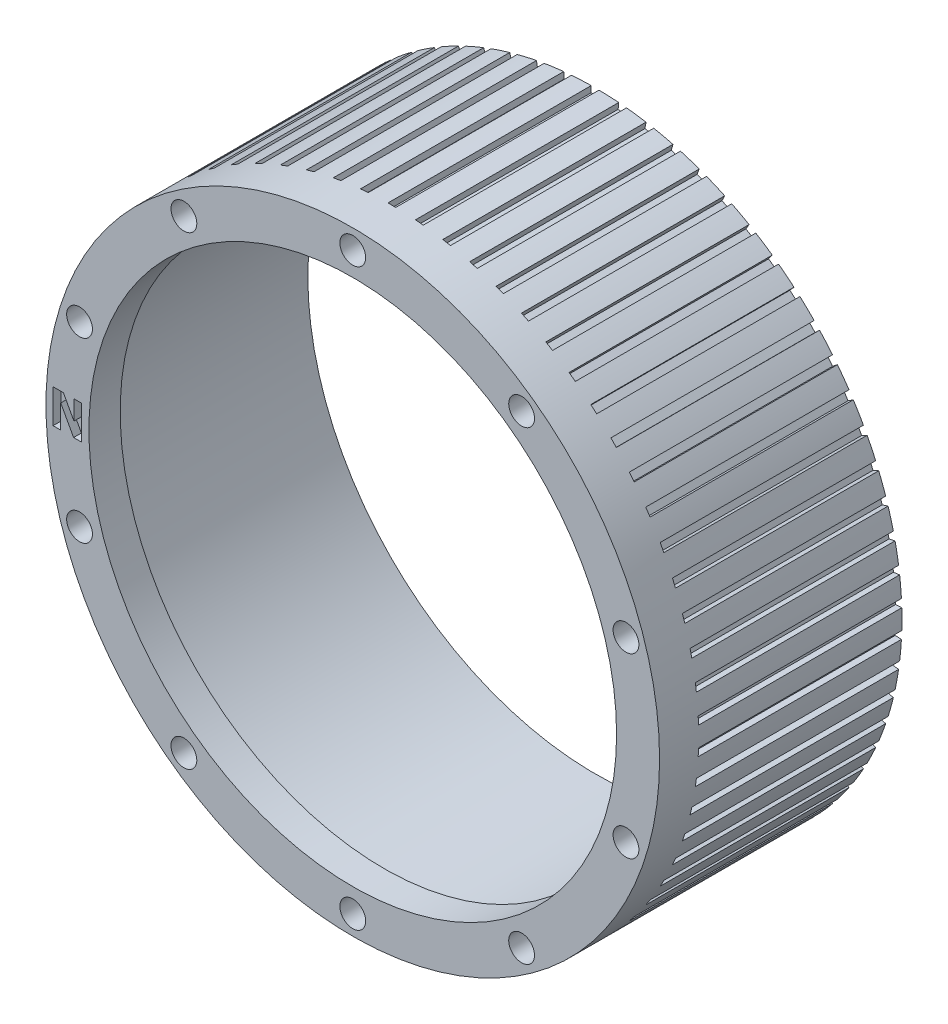
SolidWorks part; units mm, degrees
ref_plane "Front" through (0, 0, 0) normal (0, 0, 1) x (1, 0, 0)
ref_plane "Top" through (0, 0, 0) normal (0, 1, 0) x (1, 0, 0)
ref_plane "Right" through (0, 0, 0) normal (1, 0, 0) x (0, 0, -1)
sketch "Sketch1" plane through (0, 0, 0) normal (0, 0, 1) x (1, 0, 0)
  circle A0 centre (0, 0) radius 36.75 construction
  circle A1 centre (0, 0) radius 39.25
  dimension "D1" = 73.5
  dimension "D2" = 2.5
extrude "Boss-Extrude1" add sketch "Sketch1" along normal blind 31
sketch "Sketch2" plane through (0, 0, 0) normal (0, 0, -1) x (-1, 0, 0)
  circle A0 centre (0, 0) radius 36.75 construction
  circle A1 centre (0, 0) radius 36.75
extrude "Cut-Extrude1" cut sketch "Sketch2" against normal offset from surface (27 mm away) 4 up to face at (39.25, 0, 31)
sketch "Sketch3" plane through (0, 0, 31) normal (0, 0, 1) x (1, 0, 0)
  circle A0 centre (0, 0) radius 36.75 construction
  circle A1 centre (0, 0) radius 36.75 construction
  circle A2 centre (0, 0) radius 33.75
  dimension "D1" = 3
extrude "Cut-Extrude2" cut sketch "Sketch3" against normal up to surface (4 mm away) up to face at (36.75, 0, 27)
sketch "Sketch4" plane through (0, 0, 31) normal (0, 0, 1) x (1, 0, 0)
  line L0 (0, 0) -> (0, 39.25) construction
  circle A0 centre (0, 0) radius 36.75 construction
  circle A1 centre (0, 0) radius 36.75 construction
  circle A2 centre (-34.9513, -11.3564) radius 1.65
  circle A3 centre (0, 0) radius 36.75 construction
  circle A4 centre (-34.9513, 11.3564) radius 1.65
  circle A5 centre (0, 0) radius 36.75 construction
  circle A6 centre (-21.6011, 29.7314) radius 1.65
  circle A7 centre (0, 0) radius 36.75 construction
  circle A8 centre (0, 36.75) radius 1.65
  circle A9 centre (0, 0) radius 36.75 construction
  circle A10 centre (21.6011, 29.7314) radius 1.65
  circle A11 centre (0, 0) radius 36.75 construction
  circle A12 centre (34.9513, 11.3564) radius 1.65
  circle A13 centre (0, 0) radius 36.75 construction
  circle A14 centre (34.9513, -11.3564) radius 1.65
  circle A15 centre (0, 0) radius 36.75 construction
  circle A16 centre (21.6011, -29.7314) radius 1.65
  circle A17 centre (0, 0) radius 36.75 construction
  circle A18 centre (0, -36.75) radius 1.65
  circle A19 centre (0, 0) radius 36.75 construction
  circle A20 centre (-21.6011, -29.7314) radius 1.65
  circle A21 centre (0, 0) radius 39.25 construction
  dimension "D1" = 3.3
  dimension "D3" = 21.6011
  dimension "D2" = 10
extrude "Cut-Extrude3" cut sketch "Sketch4" against normal blind 2.5
sketch "Sketch5" plane through (0, 0, 0) normal (0, 0, -1) x (-1, 0, 0)
  line L0 (0, 0) -> (0, 39.25) construction
  line L1 (-0.5, 39.25) -> (0.5, 39.25)
  line L2 (-0.5, 39.25) -> (-0.5, 38.45)
  line L3 (-0.5, 38.45) -> (0.5, 38.45)
  line L4 (0.5, 39.25) -> (0.5, 38.45)
  line L5 (-0.5, 39.25) -> (0.5, 38.45) construction
  line L6 (-0.5, 38.45) -> (0.5, 39.25) construction
  line L7 (3.0204, 39.1368) -> (2.9486, 38.34)
  line L8 (3.0204, 39.1368) -> (4.0163, 39.0472)
  line L9 (4.0163, 39.0472) -> (3.9446, 38.2504)
  line L10 (2.9486, 38.34) -> (3.9446, 38.2504)
  line L11 (6.5164, 38.7085) -> (6.3735, 37.9214)
  line L12 (6.5164, 38.7085) -> (7.5003, 38.53)
  line L13 (7.5003, 38.53) -> (7.3575, 37.7428)
  line L14 (6.3735, 37.9214) -> (7.3575, 37.7428)
  line L15 (9.96, 37.9686) -> (9.7471, 37.1974)
  line L16 (9.96, 37.9686) -> (10.9239, 37.7025)
  line L17 (10.9239, 37.7025) -> (10.7111, 36.9314)
  line L18 (9.7471, 37.1974) -> (10.7111, 36.9314)
  line L19 (13.3233, 36.9229) -> (13.0422, 36.1739)
  line L20 (13.3233, 36.9229) -> (14.2596, 36.5715)
  line L21 (14.2596, 36.5715) -> (13.9785, 35.8225)
  line L22 (13.0422, 36.1739) -> (13.9785, 35.8225)
  line L23 (16.5795, 35.58) -> (16.2323, 34.8592)
  line L24 (16.5795, 35.58) -> (17.4804, 35.1461)
  line L25 (17.4804, 35.1461) -> (17.1333, 34.4253)
  line L26 (16.2323, 34.8592) -> (17.1333, 34.4253)
  line L27 (19.7021, 33.9506) -> (19.2918, 33.2638)
  line L28 (19.7021, 33.9506) -> (20.5605, 33.4377)
  line L29 (20.5605, 33.4377) -> (20.1502, 32.7509)
  line L30 (19.2918, 33.2638) -> (20.1502, 32.7509)
  line L31 (22.6661, 32.0478) -> (22.1958, 31.4006)
  line L32 (22.6661, 32.0478) -> (23.4751, 31.46)
  line L33 (23.4751, 31.46) -> (23.0049, 30.8128)
  line L34 (22.1958, 31.4006) -> (23.0049, 30.8128)
  line L35 (25.4476, 29.887) -> (24.9212, 29.2846)
  line L36 (25.4476, 29.887) -> (26.2006, 29.2291)
  line L37 (26.2006, 29.2291) -> (25.6743, 28.6266)
  line L38 (24.9212, 29.2846) -> (25.6743, 28.6266)
  line L39 (28.0242, 27.4856) -> (27.4459, 26.9328)
  line L40 (28.0242, 27.4856) -> (28.7152, 26.7628)
  line L41 (28.7152, 26.7628) -> (28.137, 26.21)
  line L42 (27.4459, 26.9328) -> (28.137, 26.21)
  line L43 (30.3751, 24.8629) -> (29.7497, 24.3641)
  line L44 (30.3751, 24.8629) -> (30.9986, 24.0811)
  line L45 (30.9986, 24.0811) -> (30.3732, 23.5823)
  line L46 (29.7497, 24.3641) -> (30.3732, 23.5823)
  line L47 (32.4816, 22.04) -> (31.8139, 21.5993)
  line L48 (32.4816, 22.04) -> (33.0324, 21.2054)
  line L49 (33.0324, 21.2054) -> (32.3648, 20.7647)
  line L50 (31.8139, 21.5993) -> (32.3648, 20.7647)
  line L51 (34.3264, 19.0396) -> (33.622, 18.6605)
  line L52 (34.3264, 19.0396) -> (34.8003, 18.159)
  line L53 (34.8003, 18.159) -> (34.0958, 17.78)
  line L54 (33.622, 18.6605) -> (34.0958, 17.78)
  line L55 (35.895, 15.886) -> (35.1593, 15.5716)
  line L56 (35.895, 15.886) -> (36.288, 14.9665)
  line L57 (36.288, 14.9665) -> (35.5524, 14.652)
  line L58 (35.1593, 15.5716) -> (35.5524, 14.652)
  line L59 (37.1745, 12.6044) -> (36.4136, 12.3572)
  line L60 (37.1745, 12.6044) -> (37.4835, 11.6534)
  line L61 (37.4835, 11.6534) -> (36.7226, 11.4062)
  line L62 (36.4136, 12.3572) -> (36.7226, 11.4062)
  line L63 (38.1547, 9.2214) -> (37.3747, 9.0434)
  line L64 (38.1547, 9.2214) -> (38.3772, 8.2465)
  line L65 (38.3772, 8.2465) -> (37.5972, 8.0685)
  line L66 (37.3747, 9.0434) -> (37.5972, 8.0685)
  line L67 (38.8277, 5.7641) -> (38.0349, 5.6567)
  line L68 (38.8277, 5.7641) -> (38.9619, 4.7732)
  line L69 (38.9619, 4.7732) -> (38.1691, 4.6658)
  line L70 (38.0349, 5.6567) -> (38.1691, 4.6658)
  line L71 (39.188, 2.2604) -> (38.3889, 2.2245)
  line L72 (39.188, 2.2604) -> (39.2329, 1.2614)
  line L73 (39.2329, 1.2614) -> (38.4337, 1.2256)
  line L74 (38.3889, 2.2245) -> (38.4337, 1.2256)
  line L75 (39.2329, -1.2614) -> (38.4337, -1.2256)
  line L76 (39.2329, -1.2614) -> (39.188, -2.2604)
  line L77 (39.188, -2.2604) -> (38.3889, -2.2245)
  line L78 (38.4337, -1.2256) -> (38.3889, -2.2245)
  line L79 (38.9619, -4.7732) -> (38.1691, -4.6658)
  line L80 (38.9619, -4.7732) -> (38.8277, -5.7641)
  line L81 (38.8277, -5.7641) -> (38.0349, -5.6567)
  line L82 (38.1691, -4.6658) -> (38.0349, -5.6567)
  line L83 (38.3772, -8.2465) -> (37.5972, -8.0685)
  line L84 (38.3772, -8.2465) -> (38.1547, -9.2214)
  line L85 (38.1547, -9.2214) -> (37.3747, -9.0434)
  line L86 (37.5972, -8.0685) -> (37.3747, -9.0434)
  line L87 (37.4835, -11.6534) -> (36.7226, -11.4062)
  line L88 (37.4835, -11.6534) -> (37.1745, -12.6044)
  line L89 (37.1745, -12.6044) -> (36.4136, -12.3572)
  line L90 (36.7226, -11.4062) -> (36.4136, -12.3572)
  line L91 (36.288, -14.9665) -> (35.5524, -14.652)
  line L92 (36.288, -14.9665) -> (35.895, -15.886)
  line L93 (35.895, -15.886) -> (35.1593, -15.5716)
  line L94 (35.5524, -14.652) -> (35.1593, -15.5716)
  line L95 (34.8003, -18.159) -> (34.0958, -17.78)
  line L96 (34.8003, -18.159) -> (34.3264, -19.0396)
  line L97 (34.3264, -19.0396) -> (33.622, -18.6605)
  line L98 (34.0958, -17.78) -> (33.622, -18.6605)
  line L99 (33.0324, -21.2054) -> (32.3648, -20.7647)
  line L100 (33.0324, -21.2054) -> (32.4816, -22.04)
  line L101 (32.4816, -22.04) -> (31.8139, -21.5993)
  line L102 (32.3648, -20.7647) -> (31.8139, -21.5993)
  line L103 (30.9986, -24.0811) -> (30.3732, -23.5823)
  line L104 (30.9986, -24.0811) -> (30.3751, -24.8629)
  line L105 (30.3751, -24.8629) -> (29.7497, -24.3641)
  line L106 (30.3732, -23.5823) -> (29.7497, -24.3641)
  line L107 (28.7152, -26.7628) -> (28.137, -26.21)
  line L108 (28.7152, -26.7628) -> (28.0242, -27.4856)
  line L109 (28.0242, -27.4856) -> (27.4459, -26.9328)
  line L110 (28.137, -26.21) -> (27.4459, -26.9328)
  line L111 (26.2006, -29.2291) -> (25.6743, -28.6266)
  line L112 (26.2006, -29.2291) -> (25.4476, -29.887)
  line L113 (25.4476, -29.887) -> (24.9212, -29.2846)
  line L114 (25.6743, -28.6266) -> (24.9212, -29.2846)
  line L115 (23.4751, -31.46) -> (23.0049, -30.8128)
  line L116 (23.4751, -31.46) -> (22.6661, -32.0478)
  line L117 (22.6661, -32.0478) -> (22.1958, -31.4006)
  line L118 (23.0049, -30.8128) -> (22.1958, -31.4006)
  line L119 (20.5605, -33.4377) -> (20.1502, -32.7509)
  line L120 (20.5605, -33.4377) -> (19.7021, -33.9506)
  line L121 (19.7021, -33.9506) -> (19.2918, -33.2638)
  line L122 (20.1502, -32.7509) -> (19.2918, -33.2638)
  line L123 (17.4804, -35.1461) -> (17.1333, -34.4253)
  line L124 (17.4804, -35.1461) -> (16.5795, -35.58)
  line L125 (16.5795, -35.58) -> (16.2323, -34.8592)
  line L126 (17.1333, -34.4253) -> (16.2323, -34.8592)
  line L127 (14.2596, -36.5715) -> (13.9785, -35.8225)
  line L128 (14.2596, -36.5715) -> (13.3233, -36.9229)
  line L129 (13.3233, -36.9229) -> (13.0422, -36.1739)
  line L130 (13.9785, -35.8225) -> (13.0422, -36.1739)
  line L131 (10.9239, -37.7025) -> (10.7111, -36.9314)
  line L132 (10.9239, -37.7025) -> (9.96, -37.9686)
  line L133 (9.96, -37.9686) -> (9.7471, -37.1974)
  line L134 (10.7111, -36.9314) -> (9.7471, -37.1974)
  line L135 (7.5003, -38.53) -> (7.3575, -37.7428)
  line L136 (7.5003, -38.53) -> (6.5164, -38.7085)
  line L137 (6.5164, -38.7085) -> (6.3735, -37.9214)
  line L138 (7.3575, -37.7428) -> (6.3735, -37.9214)
  line L139 (4.0163, -39.0472) -> (3.9446, -38.2504)
  line L140 (4.0163, -39.0472) -> (3.0204, -39.1368)
  line L141 (3.0204, -39.1368) -> (2.9486, -38.34)
  line L142 (3.9446, -38.2504) -> (2.9486, -38.34)
  line L143 (0.5, -39.25) -> (0.5, -38.45)
  line L144 (0.5, -39.25) -> (-0.5, -39.25)
  line L145 (-0.5, -39.25) -> (-0.5, -38.45)
  line L146 (0.5, -38.45) -> (-0.5, -38.45)
  line L147 (-3.0204, -39.1368) -> (-2.9486, -38.34)
  line L148 (-3.0204, -39.1368) -> (-4.0163, -39.0472)
  line L149 (-4.0163, -39.0472) -> (-3.9446, -38.2504)
  line L150 (-2.9486, -38.34) -> (-3.9446, -38.2504)
  line L151 (-6.5164, -38.7085) -> (-6.3735, -37.9214)
  line L152 (-6.5164, -38.7085) -> (-7.5003, -38.53)
  line L153 (-7.5003, -38.53) -> (-7.3575, -37.7428)
  line L154 (-6.3735, -37.9214) -> (-7.3575, -37.7428)
  line L155 (-9.96, -37.9686) -> (-9.7471, -37.1974)
  line L156 (-9.96, -37.9686) -> (-10.9239, -37.7025)
  line L157 (-10.9239, -37.7025) -> (-10.7111, -36.9314)
  line L158 (-9.7471, -37.1974) -> (-10.7111, -36.9314)
  line L159 (-13.3233, -36.9229) -> (-13.0422, -36.1739)
  line L160 (-13.3233, -36.9229) -> (-14.2596, -36.5715)
  line L161 (-14.2596, -36.5715) -> (-13.9785, -35.8225)
  line L162 (-13.0422, -36.1739) -> (-13.9785, -35.8225)
  line L163 (-16.5795, -35.58) -> (-16.2323, -34.8592)
  line L164 (-16.5795, -35.58) -> (-17.4804, -35.1461)
  line L165 (-17.4804, -35.1461) -> (-17.1333, -34.4253)
  line L166 (-16.2323, -34.8592) -> (-17.1333, -34.4253)
  line L167 (-19.7021, -33.9506) -> (-19.2918, -33.2638)
  line L168 (-19.7021, -33.9506) -> (-20.5605, -33.4377)
  line L169 (-20.5605, -33.4377) -> (-20.1502, -32.7509)
  line L170 (-19.2918, -33.2638) -> (-20.1502, -32.7509)
  line L171 (-22.6661, -32.0478) -> (-22.1958, -31.4006)
  line L172 (-22.6661, -32.0478) -> (-23.4751, -31.46)
  line L173 (-23.4751, -31.46) -> (-23.0049, -30.8128)
  line L174 (-22.1958, -31.4006) -> (-23.0049, -30.8128)
  line L175 (-25.4476, -29.887) -> (-24.9212, -29.2846)
  line L176 (-25.4476, -29.887) -> (-26.2006, -29.2291)
  line L177 (-26.2006, -29.2291) -> (-25.6743, -28.6266)
  line L178 (-24.9212, -29.2846) -> (-25.6743, -28.6266)
  line L179 (-28.0242, -27.4856) -> (-27.4459, -26.9328)
  line L180 (-28.0242, -27.4856) -> (-28.7152, -26.7628)
  line L181 (-28.7152, -26.7628) -> (-28.137, -26.21)
  line L182 (-27.4459, -26.9328) -> (-28.137, -26.21)
  line L183 (-30.3751, -24.8629) -> (-29.7497, -24.3641)
  line L184 (-30.3751, -24.8629) -> (-30.9986, -24.0811)
  line L185 (-30.9986, -24.0811) -> (-30.3732, -23.5823)
  line L186 (-29.7497, -24.3641) -> (-30.3732, -23.5823)
  line L187 (-32.4816, -22.04) -> (-31.8139, -21.5993)
  line L188 (-32.4816, -22.04) -> (-33.0324, -21.2054)
  line L189 (-33.0324, -21.2054) -> (-32.3648, -20.7647)
  line L190 (-31.8139, -21.5993) -> (-32.3648, -20.7647)
  line L191 (-34.3264, -19.0396) -> (-33.622, -18.6605)
  line L192 (-34.3264, -19.0396) -> (-34.8003, -18.159)
  line L193 (-34.8003, -18.159) -> (-34.0958, -17.78)
  line L194 (-33.622, -18.6605) -> (-34.0958, -17.78)
  line L195 (-35.895, -15.886) -> (-35.1593, -15.5716)
  line L196 (-35.895, -15.886) -> (-36.288, -14.9665)
  line L197 (-36.288, -14.9665) -> (-35.5524, -14.652)
  line L198 (-35.1593, -15.5716) -> (-35.5524, -14.652)
  line L199 (-37.1745, -12.6044) -> (-36.4136, -12.3572)
  line L200 (-37.1745, -12.6044) -> (-37.4835, -11.6534)
  line L201 (-37.4835, -11.6534) -> (-36.7226, -11.4062)
  line L202 (-36.4136, -12.3572) -> (-36.7226, -11.4062)
  line L203 (-38.1547, -9.2214) -> (-37.3747, -9.0434)
  line L204 (-38.1547, -9.2214) -> (-38.3772, -8.2465)
  line L205 (-38.3772, -8.2465) -> (-37.5972, -8.0685)
  line L206 (-37.3747, -9.0434) -> (-37.5972, -8.0685)
  line L207 (-38.8277, -5.7641) -> (-38.0349, -5.6567)
  line L208 (-38.8277, -5.7641) -> (-38.9619, -4.7732)
  line L209 (-38.9619, -4.7732) -> (-38.1691, -4.6658)
  line L210 (-38.0349, -5.6567) -> (-38.1691, -4.6658)
  line L211 (-39.188, -2.2604) -> (-38.3889, -2.2245)
  line L212 (-39.188, -2.2604) -> (-39.2329, -1.2614)
  line L213 (-39.2329, -1.2614) -> (-38.4337, -1.2256)
  line L214 (-38.3889, -2.2245) -> (-38.4337, -1.2256)
  line L215 (-39.2329, 1.2614) -> (-38.4337, 1.2256)
  line L216 (-39.2329, 1.2614) -> (-39.188, 2.2604)
  line L217 (-39.188, 2.2604) -> (-38.3889, 2.2245)
  line L218 (-38.4337, 1.2256) -> (-38.3889, 2.2245)
  line L219 (-38.9619, 4.7732) -> (-38.1691, 4.6658)
  line L220 (-38.9619, 4.7732) -> (-38.8277, 5.7641)
  line L221 (-38.8277, 5.7641) -> (-38.0349, 5.6567)
  line L222 (-38.1691, 4.6658) -> (-38.0349, 5.6567)
  line L223 (-38.3772, 8.2465) -> (-37.5972, 8.0685)
  line L224 (-38.3772, 8.2465) -> (-38.1547, 9.2214)
  line L225 (-38.1547, 9.2214) -> (-37.3747, 9.0434)
  line L226 (-37.5972, 8.0685) -> (-37.3747, 9.0434)
  line L227 (-37.4835, 11.6534) -> (-36.7226, 11.4062)
  line L228 (-37.4835, 11.6534) -> (-37.1745, 12.6044)
  line L229 (-37.1745, 12.6044) -> (-36.4136, 12.3572)
  line L230 (-36.7226, 11.4062) -> (-36.4136, 12.3572)
  line L231 (-36.288, 14.9665) -> (-35.5524, 14.652)
  line L232 (-36.288, 14.9665) -> (-35.895, 15.886)
  line L233 (-35.895, 15.886) -> (-35.1593, 15.5716)
  line L234 (-35.5524, 14.652) -> (-35.1593, 15.5716)
  line L235 (-34.8003, 18.159) -> (-34.0958, 17.78)
  line L236 (-34.8003, 18.159) -> (-34.3264, 19.0396)
  line L237 (-34.3264, 19.0396) -> (-33.622, 18.6605)
  line L238 (-34.0958, 17.78) -> (-33.622, 18.6605)
  line L239 (-33.0324, 21.2054) -> (-32.3648, 20.7647)
  line L240 (-33.0324, 21.2054) -> (-32.4816, 22.04)
  line L241 (-32.4816, 22.04) -> (-31.8139, 21.5993)
  line L242 (-32.3648, 20.7647) -> (-31.8139, 21.5993)
  line L243 (-30.9986, 24.0811) -> (-30.3732, 23.5823)
  line L244 (-30.9986, 24.0811) -> (-30.3751, 24.8629)
  line L245 (-30.3751, 24.8629) -> (-29.7497, 24.3641)
  line L246 (-30.3732, 23.5823) -> (-29.7497, 24.3641)
  line L247 (-28.7152, 26.7628) -> (-28.137, 26.21)
  line L248 (-28.7152, 26.7628) -> (-28.0242, 27.4856)
  line L249 (-28.0242, 27.4856) -> (-27.4459, 26.9328)
  line L250 (-28.137, 26.21) -> (-27.4459, 26.9328)
  line L251 (-26.2006, 29.2291) -> (-25.6743, 28.6266)
  line L252 (-26.2006, 29.2291) -> (-25.4476, 29.887)
  line L253 (-25.4476, 29.887) -> (-24.9212, 29.2846)
  line L254 (-25.6743, 28.6266) -> (-24.9212, 29.2846)
  line L255 (-23.4751, 31.46) -> (-23.0049, 30.8128)
  line L256 (-23.4751, 31.46) -> (-22.6661, 32.0478)
  line L257 (-22.6661, 32.0478) -> (-22.1958, 31.4006)
  line L258 (-23.0049, 30.8128) -> (-22.1958, 31.4006)
  line L259 (-20.5605, 33.4377) -> (-20.1502, 32.7509)
  line L260 (-20.5605, 33.4377) -> (-19.7021, 33.9506)
  line L261 (-19.7021, 33.9506) -> (-19.2918, 33.2638)
  line L262 (-20.1502, 32.7509) -> (-19.2918, 33.2638)
  line L263 (-17.4804, 35.1461) -> (-17.1333, 34.4253)
  line L264 (-17.4804, 35.1461) -> (-16.5795, 35.58)
  line L265 (-16.5795, 35.58) -> (-16.2323, 34.8592)
  line L266 (-17.1333, 34.4253) -> (-16.2323, 34.8592)
  line L267 (-14.2596, 36.5715) -> (-13.9785, 35.8225)
  line L268 (-14.2596, 36.5715) -> (-13.3233, 36.9229)
  line L269 (-13.3233, 36.9229) -> (-13.0422, 36.1739)
  line L270 (-13.9785, 35.8225) -> (-13.0422, 36.1739)
  line L271 (-10.9239, 37.7025) -> (-10.7111, 36.9314)
  line L272 (-10.9239, 37.7025) -> (-9.96, 37.9686)
  line L273 (-9.96, 37.9686) -> (-9.7471, 37.1974)
  line L274 (-10.7111, 36.9314) -> (-9.7471, 37.1974)
  line L275 (-7.5003, 38.53) -> (-7.3575, 37.7428)
  line L276 (-7.5003, 38.53) -> (-6.5164, 38.7085)
  line L277 (-6.5164, 38.7085) -> (-6.3735, 37.9214)
  line L278 (-7.3575, 37.7428) -> (-6.3735, 37.9214)
  line L279 (-4.0163, 39.0472) -> (-3.9446, 38.2504)
  line L280 (-4.0163, 39.0472) -> (-3.0204, 39.1368)
  line L281 (-3.0204, 39.1368) -> (-2.9486, 38.34)
  line L282 (-3.9446, 38.2504) -> (-2.9486, 38.34)
  circle A1 centre (0, 0) radius 39.25 construction
  point P0 (0, 38.85)
  point P10 (0, 39.25)
  dimension "D1" = 0.8
  dimension "D2" = 1
  dimension "D3" = 70
extrude "Cut-Extrude4" cut sketch "Sketch5" against normal offset from surface (26 mm away) 5 up to face at (1.65, -36.75, 31)
sketch "Sketch6" plane through (0, 0, 31) normal (0, 0, 1) x (1, 0, 0)
  text T0 "N" font "Tahoma" height in points 16
extrude "Cut-Extrude5" cut sketch "Sketch6" against normal blind 1
